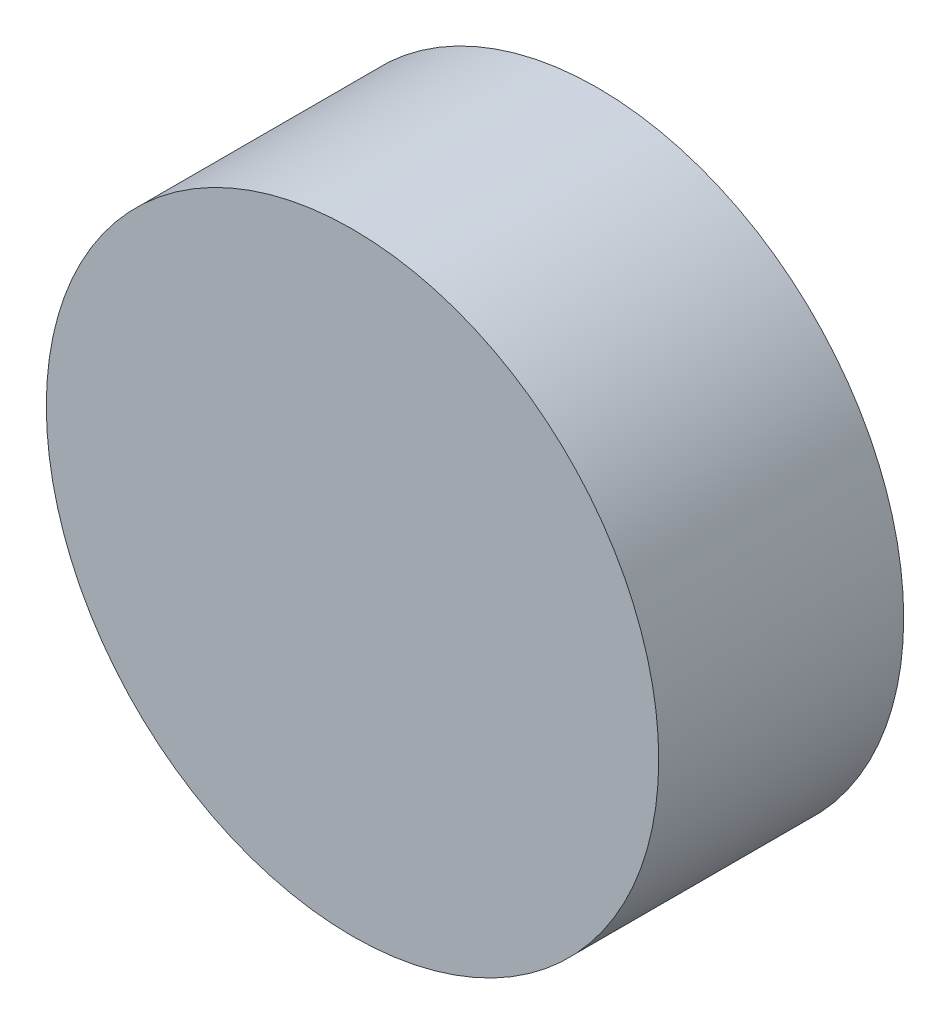
SolidWorks part; units mm, degrees
ref_plane "Přední rovina" through (0, 0, 0) normal (0, 0, 1) x (1, 0, 0)
ref_plane "Horní rovina" through (0, 0, 0) normal (0, 1, 0) x (1, 0, 0)
ref_plane "Pravá rovina" through (0, 0, 0) normal (1, 0, 0) x (0, 0, -1)
sketch "Sketch1" plane through (0, 0, 0) normal (0, 1, 0) x (1, 0, 0)
  line L1 (-25, 0) -> (-15, 0)
  line L2 (-25, 0) -> (-25, -20)
  line L3 (-25, -20) -> (0, -20)
  line L6 (-15, 0) -> (-15, -10)
  line L7 (-15, -10) -> (0, -10)
  line L9 (0, 0) -> (0, -20) construction
  line L13 (0, -20) -> (0, -10)
  point P3 (0, -10)
  dimension "D1" = 25
  dimension "D2" = 10
  dimension "D3" = 10
  dimension "D4" = 10
revolve "Revolve1" add sketch "Sketch1" angle 360 about L9
